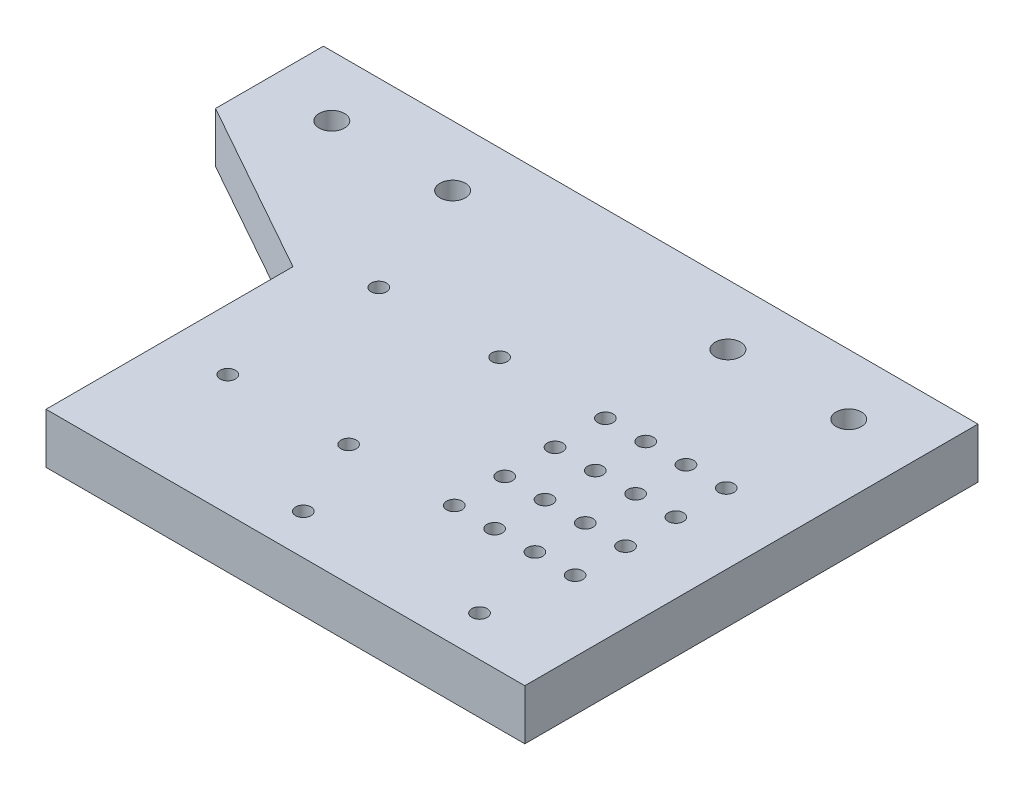
SolidWorks part; units mm, degrees
ref_plane "Front Plane" through (0, 0, 0) normal (0, 0, 1) x (1, 0, 0)
ref_plane "Top Plane" through (0, 0, 0) normal (0, 1, 0) x (1, 0, 0)
ref_plane "Right Plane" through (0, 0, 0) normal (1, 0, 0) x (0, 0, -1)
sketch "草图1" plane through (0, 0, 0) normal (0, 1, 0) x (1, 0, 0)
  line L0 (31.7389, -17.2036) -> (-38.2611, -17.2036)
  line L1 (-98.2611, 72.7964) -> (31.7389, 72.7964)
  line L2 (-98.2611, 72.7964) -> (-98.2611, 51.371)
  line L3 (-38.2611, -17.2036) -> (31.7389, -17.2036)
  line L4 (31.7389, 28.4691) -> (31.7389, -17.2036)
  line L5 (-98.2611, 72.7964) -> (-98.2611, 51.371)
  line L6 (-63.3581, 31.8401) -> (-63.3581, -17.2036)
  line L7 (14.7389, -9.2036) -> (-20.2611, -9.2036)
  line L8 (31.7389, -17.2036) -> (14.7389, -17.2036)
  line L9 (31.7389, -17.2036) -> (31.7389, -9.2036)
  line L10 (31.7389, -9.2036) -> (14.7389, -9.2036)
  line L11 (14.7389, -17.2036) -> (14.7389, -9.2036)
  line L12 (18.0722, 60.7964) -> (-5.9278, 60.7964)
  line L13 (31.7389, 72.7964) -> (18.0722, 72.7964)
  line L14 (31.7389, 72.7964) -> (31.7389, 60.7964)
  line L15 (31.7389, 60.7964) -> (18.0722, 60.7964)
  line L16 (18.0722, 72.7964) -> (18.0722, 60.7964)
  line L17 (-5.9278, 60.7964) -> (-5.9278, 58.2714)
  line L18 (-7.4831, 45.7964) -> (-5.9278, 45.7964)
  line L19 (-33.2611, 72.7964) -> (-33.2611, 51.371)
  line L20 (31.7389, 60.7964) -> (31.7389, 28.4691)
  line L21 (-98.2611, 51.371) -> (-63.3581, 31.8401)
  line L22 (-6.2611, 36.7964) -> (-51.2611, 36.7964)
  line L23 (31.7389, -17.2036) -> (17.7389, -17.2036)
  line L24 (31.7389, -17.2036) -> (31.7389, 6.7964)
  line L25 (31.7389, 6.7964) -> (17.7389, 6.7964)
  line L26 (17.7389, -17.2036) -> (17.7389, 6.7964)
  line L27 (17.7389, 6.7964) -> (-6.2611, 6.7964)
  line L28 (17.7389, 6.7964) -> (17.7389, 36.7964)
  line L29 (17.7389, 36.7964) -> (-6.2611, 36.7964)
  line L30 (-6.2611, 6.7964) -> (-6.2611, 36.7964)
  line L31 (-63.3581, -17.2036) -> (-38.2611, -17.2036)
  line L32 (-39.2611, 6.7964) -> (-39.2611, 9.1556)
  line L33 (-51.2611, 36.7964) -> (-27.2611, 36.7964)
  line L34 (-51.2611, 36.7964) -> (-51.2611, 6.7964)
  line L35 (-51.2611, 6.7964) -> (-27.2611, 6.7964)
  line L36 (-27.2611, 36.7964) -> (-27.2611, 6.7964)
  line L37 (-6.2611, 36.7964) -> (1.7366, 36.7964)
  line L38 (1.7366, 36.7964) -> (9.7366, 36.7964)
  line L39 (-6.2611, 36.7964) -> (-6.2611, 26.7964)
  line L40 (-6.2611, 26.7964) -> (-6.2611, 16.7964)
  line L41 (-6.2611, 21.7964) -> (17.7389, 21.7964)
  line L42 (1.7366, 36.7964) -> (1.7366, 21.7964)
  line L43 (9.7366, 36.7964) -> (9.7366, 21.7964)
  line L44 (-6.2611, 26.7964) -> (17.7389, 26.7964)
  circle A0 centre (-20.2611, -9.2036) radius 1.525
  circle A1 centre (14.7389, -9.2036) radius 1.525
  circle A2 centre (-5.9278, 60.7964) radius 2.525
  circle A3 centre (18.0722, 60.7964) radius 2.525
  circle A8 centre (-84.5943, 60.7964) radius 2.525
  circle A9 centre (-60.5943, 60.7964) radius 2.525
  circle A10 centre (17.7389, 6.7964) radius 1.525
  circle A11 centre (17.7389, 36.7964) radius 1.525
  circle A12 centre (-6.2611, 36.7964) radius 1.525
  circle A13 centre (-6.2611, 6.7964) radius 1.525
  circle A14 centre (-51.2611, 36.7964) radius 1.525
  circle A15 centre (-51.2611, 6.7964) radius 1.525
  circle A16 centre (-27.2611, 6.7964) radius 1.525
  circle A17 centre (-27.2611, 36.7964) radius 1.525
  circle A18 centre (1.7366, 36.7964) radius 1.525
  circle A19 centre (9.7366, 36.7964) radius 1.525
  circle A20 centre (-6.2611, 26.7964) radius 1.525
  circle A21 centre (-6.2611, 16.7964) radius 1.525
  circle A22 centre (1.7366, 26.7964) radius 1.525
  circle A23 centre (9.7366, 26.7964) radius 1.525
  circle A24 centre (17.7389, 26.7964) radius 1.525
  circle A25 centre (1.7366, 6.7964) radius 1.525
  circle A26 centre (9.7366, 6.7964) radius 1.525
  circle A27 centre (17.7389, 16.7964) radius 1.525
  circle A28 centre (9.7366, 16.7964) radius 1.525
  circle A29 centre (1.7366, 16.7964) radius 1.525
  dimension "D8" = 3.05
  dimension "D9" = 3.05
  dimension "D12" = 5.05
  dimension "D13" = 5.05
  dimension "D15" = 3.05
  dimension "D17" = 3.05
  dimension "D18" = 3.05
  dimension "D19" = 3.05
  dimension "D23" = 3.05
  dimension "D24" = 3.05
  dimension "D26" = 3.05
  dimension "D27" = 3.05
  dimension "D30" = 3.05
  dimension "D31" = 3.05
  dimension "D32" = 3.05
  dimension "D33" = 3.05
  dimension "D34" = 3.05
  dimension "D1" = 130
  dimension "D2" = 90
  dimension "D3" = 70
  dimension "D4" = 14
  dimension "D5" = 8
  dimension "D6" = 17
  dimension "D7" = 35
  dimension "D10" = 12
  dimension "D11" = 24
  dimension "D14" = 24
  dimension "D16" = 24
  dimension "D20" = 45
  dimension "D21" = 24
  dimension "D22" = 30
  dimension "D25" = 8
  dimension "D28" = 10
  dimension "D29" = 10
extrude "凸台-拉伸1" add sketch "草图1" along normal blind 10
